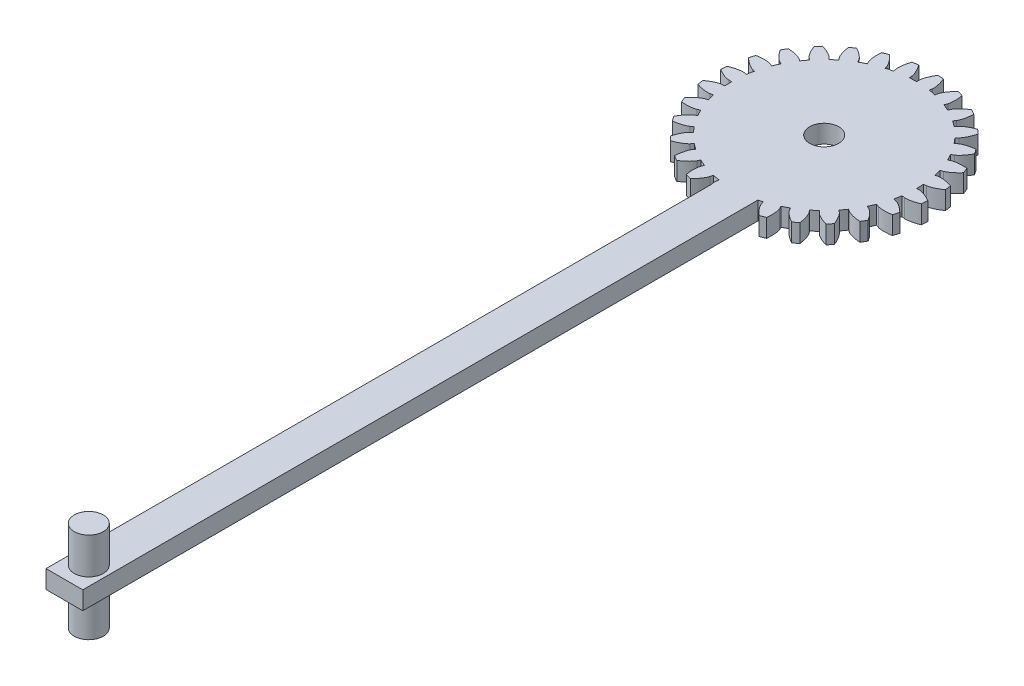
SolidWorks part; units mm, degrees
ref_plane "前视基准面" through (0, 0, 0) normal (0, 0, 1) x (1, 0, 0)
ref_plane "上视基准面" through (0, 0, 0) normal (0, 1, 0) x (1, 0, 0)
ref_plane "右视基准面" through (0, 0, 0) normal (1, 0, 0) x (0, 0, -1)
other "Configuration Table"
sketch "草图1" plane through (0, 0, 0) normal (0, 1, 0) x (1, 0, 0)
  line L0 (0, 0) -> (0.4992, 27.8082) construction
  line L1 (0, 0) -> (2.0715, 27.9233) construction
  line L2 (0, 0) -> (5.5923, 29.6778) construction
  circle A1 centre (0, 0) radius 30
  circle A2 centre (0, 0) radius 25.5
  circle A3 centre (0, 0) radius 28
  spline S0 degree 4 poles (0, 26.3114) (0.0005, 26.3327) (0.0033, 26.3925) (0.0143, 26.5052) (0.0405, 26.6883) (0.1066, 27.0262) (0.2428, 27.5315) (0.4372, 28.0765) (0.6818, 28.6409) (0.9223, 29.1277) (1.1281, 29.5103) (1.3926, 29.9661) (1.733, 30.5031) (2.1599, 31.113) (2.6837, 31.7862) (3.2497, 32.4456) (3.8445, 33.0787) (4.4662, 33.686) (5.1111, 34.2675) (5.6956, 34.7547) (6.2075, 35.1557) (6.6446, 35.4811) (6.994, 35.7325) (7.3574, 35.9834) (7.7076, 36.2182) (8.0916, 36.4641) (8.4279, 36.6743) (8.9316, 36.9744) (9.2362, 37.1482) (9.7285, 37.4218) (9.9511, 37.5362) (10.152, 37.643) (10.2116, 37.6724) (10.2551, 37.6949) (10.2786, 37.7071) knots 0 0 0 0 0 0.005377 0.015084 0.028532 0.04661 0.092111 0.146842 0.174209 0.201575 0.228941 0.256307 0.307035 0.361767 0.4165 0.471232 0.525964 0.580697 0.635429 0.690161 0.717528 0.744894 0.77226 0.799626 0.826992 0.854358 0.881725 0.909091 0.954545 0.977273 0.988636 0.994318 1 1 1 1 1 construction
  spline S1 degree 4 poles (0, 26.3114) (0.0005, 26.3327) (0.0033, 26.3925) (0.0143, 26.5052) (0.0405, 26.6883) (0.1066, 27.0262) (0.2428, 27.5315) (0.4372, 28.0765) (0.6818, 28.6409) (0.9571, 29.1981) (1.1516, 29.5526) (1.3012, 29.8077) (1.3986, 29.9674) knots 0 0 0 0 0 0.005377 0.015084 0.028532 0.04661 0.092111 0.146842 0.174209 0.201575 0.248726 0.248726 0.248726 0.248726 0.248726
  spline S2 degree 1 poles (0, 26.3114) (0, 25.5) knots 0 0 1 1
  spline S3 degree 1 poles (3.8825, 26.0234) (3.7628, 25.2209) knots 0 0 1 1
  spline S4 degree 4 poles (3.8825, 26.0234) (3.8852, 26.0445) (3.8912, 26.1041) (3.8969, 26.2172) (3.8981, 26.4022) (3.8826, 26.7461) (3.8224, 27.2659) (3.7106, 27.8337) (3.5519, 28.428) (3.3618, 29.0197) (3.2218, 29.3991) (3.1115, 29.6734) (3.0387, 29.8457) knots 0 0 0 0 0 0.005377 0.015084 0.028532 0.04661 0.092111 0.146842 0.174209 0.201575 0.248726 0.248726 0.248726 0.248726 0.248726
  spline S5 degree 1 poles (5.8548, 25.6517) (5.6743, 24.8607) knots 0 0 1 1
  spline S6 degree 4 poles (5.8548, 25.6517) (5.86, 25.6724) (5.8761, 25.7301) (5.9119, 25.8375) (5.9782, 26.0102) (6.1178, 26.3249) (6.363, 26.7872) (6.6738, 27.2753) (7.0379, 27.7711) (7.4303, 28.2531) (7.6988, 28.5554) (7.9014, 28.7708) (8.0319, 28.9048) knots 0 0 0 0 0 0.005377 0.015084 0.028532 0.04661 0.092111 0.146842 0.174209 0.201575 0.248726 0.248726 0.248726 0.248726 0.248726
  dimension "D1" = 56
  dimension "D2" = 60
  dimension "D3" = 51
  dimension "D4" = 3.214
  dimension "D5" = 9.643
sketch "草图2" plane through (0, 0, 0) normal (0, 1, 0) x (1, 0, 0)
  circle A0 centre (0, 0) radius 25.5 construction
  circle A1 centre (0, 0) radius 30 construction
  arc A2 (5.6743, 24.8607) -> (3.7628, 25.2209) centre (0, 0) ccw
  arc A3 (3.0387, 29.8457) -> (1.3986, 29.9674) centre (0, 0) ccw
  arc A4 (9.6038, 28.4212) -> (8.0319, 28.9048) centre (0, 0) ccw
  arc A5 (11.064, 22.9747) -> (9.2806, 23.7512) centre (0, 0) ccw
  arc A6 (15.6873, 25.5716) -> (14.2625, 26.3928) centre (0, 0) ccw
  arc A7 (15.899, 19.9367) -> (14.333, 21.0906) centre (0, 0) ccw
  arc A8 (20.9842, 21.4397) -> (19.7778, 22.5574) centre (0, 0) ccw
  arc A9 (19.9367, 15.899) -> (18.6668, 17.3724) centre (0, 0) ccw
  arc A10 (25.2289, 16.2328) -> (24.3015, 17.5909) centre (0, 0) ccw
  arc A11 (22.9747, 11.064) -> (22.0645, 12.7831) centre (0, 0) ccw
  arc A12 (28.2085, 10.2118) -> (27.6065, 11.7423) centre (0, 0) ccw
  arc A13 (24.8607, 5.6743) -> (24.3558, 7.5528) centre (0, 0) ccw
  arc A14 (29.7736, 3.6788) -> (29.5273, 5.3048) centre (0, 0) ccw
  arc A15 (25.5, 0) -> (25.4258, 1.9437) centre (0, 0) ccw
  arc A16 (29.8457, -3.0387) -> (29.9674, -1.3986) centre (0, 0) ccw
  arc A17 (24.8607, -5.6743) -> (25.2209, -3.7628) centre (0, 0) ccw
  arc A18 (28.4212, -9.6038) -> (28.9048, -8.0319) centre (0, 0) ccw
  arc A19 (22.9747, -11.064) -> (23.7512, -9.2806) centre (0, 0) ccw
  arc A20 (25.5716, -15.6873) -> (26.3928, -14.2625) centre (0, 0) ccw
  arc A21 (19.9367, -15.899) -> (21.0906, -14.333) centre (0, 0) ccw
  arc A22 (21.4397, -20.9842) -> (22.5574, -19.7778) centre (0, 0) ccw
  arc A23 (15.899, -19.9367) -> (17.3724, -18.6668) centre (0, 0) ccw
  arc A24 (16.2328, -25.2289) -> (17.5909, -24.3015) centre (0, 0) ccw
  arc A25 (11.064, -22.9747) -> (12.7831, -22.0645) centre (0, 0) ccw
  arc A26 (10.2118, -28.2085) -> (11.7423, -27.6065) centre (0, 0) ccw
  arc A27 (5.6743, -24.8607) -> (7.5528, -24.3558) centre (0, 0) ccw
  arc A28 (3.6788, -29.7736) -> (5.3048, -29.5273) centre (0, 0) ccw
  arc A29 (0, -25.5) -> (1.9437, -25.4258) centre (0, 0) ccw
  arc A30 (-3.0387, -29.8457) -> (-1.3986, -29.9674) centre (0, 0) ccw
  arc A31 (-5.6743, -24.8607) -> (-3.7628, -25.2209) centre (0, 0) ccw
  arc A32 (-9.6038, -28.4212) -> (-8.0319, -28.9048) centre (0, 0) ccw
  arc A33 (-11.064, -22.9747) -> (-9.2806, -23.7512) centre (0, 0) ccw
  arc A34 (-15.6873, -25.5716) -> (-14.2625, -26.3928) centre (0, 0) ccw
  arc A35 (-15.899, -19.9367) -> (-14.333, -21.0906) centre (0, 0) ccw
  arc A36 (-20.9842, -21.4397) -> (-19.7778, -22.5574) centre (0, 0) ccw
  arc A37 (-19.9367, -15.899) -> (-18.6668, -17.3724) centre (0, 0) ccw
  arc A38 (-25.2289, -16.2328) -> (-24.3015, -17.5909) centre (0, 0) ccw
  arc A39 (-22.9747, -11.064) -> (-22.0645, -12.7831) centre (0, 0) ccw
  arc A40 (-28.2085, -10.2118) -> (-27.6065, -11.7423) centre (0, 0) ccw
  arc A41 (-24.8607, -5.6743) -> (-24.3558, -7.5528) centre (0, 0) ccw
  arc A42 (-29.7736, -3.6788) -> (-29.5273, -5.3048) centre (0, 0) ccw
  arc A43 (-25.5, 0) -> (-25.4258, -1.9437) centre (0, 0) ccw
  arc A44 (-29.8457, 3.0387) -> (-29.9674, 1.3986) centre (0, 0) ccw
  arc A45 (-24.8607, 5.6743) -> (-25.2209, 3.7628) centre (0, 0) ccw
  arc A46 (-28.4212, 9.6038) -> (-28.9048, 8.0319) centre (0, 0) ccw
  arc A47 (-22.9747, 11.064) -> (-23.7512, 9.2806) centre (0, 0) ccw
  arc A48 (-25.5716, 15.6873) -> (-26.3928, 14.2625) centre (0, 0) ccw
  arc A49 (-19.9367, 15.899) -> (-21.0906, 14.333) centre (0, 0) ccw
  arc A50 (-21.4397, 20.9842) -> (-22.5574, 19.7778) centre (0, 0) ccw
  arc A51 (-15.899, 19.9367) -> (-17.3724, 18.6668) centre (0, 0) ccw
  arc A52 (-16.2328, 25.2289) -> (-17.5909, 24.3015) centre (0, 0) ccw
  arc A53 (-11.064, 22.9747) -> (-12.7831, 22.0645) centre (0, 0) ccw
  arc A54 (-10.2118, 28.2085) -> (-11.7423, 27.6065) centre (0, 0) ccw
  arc A55 (-5.6743, 24.8607) -> (-7.5528, 24.3558) centre (0, 0) ccw
  arc A56 (-3.6788, 29.7736) -> (-5.3048, 29.5273) centre (0, 0) ccw
  arc A57 (0, 25.5) -> (-1.9437, 25.4258) centre (0, 0) ccw
  spline S2 degree 1 poles (446.5585, 2993.172) (-438.9084, -2941.8952) knots -3697.329683 -3697.329683 3698.289139 3698.289139 only from (3.8825, 26.0234) to (3.7628, 25.2209) construction
  spline S3 degree 4 poles (-2963.5983, 460.6318) (-43.9294, 27.4595) (2.5359, 22.6625) (3.8865, 24.4837) (3.8981, 26.4022) (3.8826, 26.7461) (3.8224, 27.2659) (3.7106, 27.8337) (3.5519, 28.428) (-1.991, 45.6841) (-39.6557, 51.7161) (84.7425, 26.7975) (-2996.3003, -25.1272) knots -0.436845 -0.436845 -0.436845 -0.436845 -0.436845 0.005377 0.015084 0.028532 0.04661 0.092111 0.146842 0.174209 0.201575 4.659416 4.659416 4.659416 4.659416 4.659416 only from (3.8825, 26.0234) to (3.0387, 29.8457) construction
  spline S4 degree 1 poles (0, 3026.3002) (0, -2974.4559) knots -3697.329683 -3697.329683 3698.289139 3698.289139 only from (0, 26.3114) to (0, 25.5) construction
  spline S5 degree 4 poles (2999.1269, 18.2832) (47.5004, 20.6767) (0.8359, 22.7886) (-0.2312, 24.7892) (0.0405, 26.6883) (0.1066, 27.0262) (0.2428, 27.5315) (0.4372, 28.0765) (0.6818, 28.6409) (8.7103, 44.8902) (46.8528, 45.2984) (-79.8606, 39.0087) (2959.7927, -466.9838) knots -0.436845 -0.436845 -0.436845 -0.436845 -0.436845 0.005377 0.015084 0.028532 0.04661 0.092111 0.146842 0.174209 0.201575 4.659416 4.659416 4.659416 4.659416 4.659416 only from (0, 26.3114) to (1.3986, 29.9674) construction
  spline S6 degree 4 poles (5.8548, 25.6517) (5.86, 25.6724) (5.8761, 25.7301) (5.9119, 25.8375) (5.9782, 26.0102) (6.1178, 26.3249) (6.363, 26.7872) (6.6738, 27.2753) (7.0379, 27.7711) (7.4303, 28.2531) (7.6988, 28.5554) (7.9014, 28.7708) (8.0319, 28.9048) knots 0 0 0 0 0 0.005377 0.015084 0.028532 0.04661 0.092111 0.146842 0.174209 0.201575 0.248726 0.248726 0.248726 0.248726 0.248726
  spline S7 degree 1 poles (5.8548, 25.6517) (5.6743, 24.8607) knots 0 0 1 1
  spline S8 degree 1 poles (3.8825, 26.0234) (3.7628, 25.2209) knots 0 0 1 1
  spline S9 degree 4 poles (3.8825, 26.0234) (3.8852, 26.0445) (3.8912, 26.1041) (3.8969, 26.2172) (3.8981, 26.4022) (3.8826, 26.7461) (3.8224, 27.2659) (3.7106, 27.8337) (3.5519, 28.428) (3.3618, 29.0197) (3.2218, 29.3991) (3.1115, 29.6734) (3.0387, 29.8457) knots 0 0 0 0 0 0.005377 0.015084 0.028532 0.04661 0.092111 0.146842 0.174209 0.201575 0.248726 0.248726 0.248726 0.248726 0.248726
  spline S10 degree 1 poles (0, 26.3114) (0, 25.5) knots 0 0 1 1
  spline S11 degree 4 poles (0, 26.3114) (0.0005, 26.3327) (0.0033, 26.3925) (0.0143, 26.5052) (0.0405, 26.6883) (0.1066, 27.0262) (0.2428, 27.5315) (0.4372, 28.0765) (0.6818, 28.6409) (0.9571, 29.1981) (1.1516, 29.5526) (1.3012, 29.8077) (1.3986, 29.9674) knots 0 0 0 0 0 0.005377 0.015084 0.028532 0.04661 0.092111 0.146842 0.174209 0.201575 0.248726 0.248726 0.248726 0.248726 0.248726
  spline S12 degree 4 poles (9.5759, 24.507) (9.5832, 24.527) (9.6024, 24.5837) (9.6331, 24.6927) (9.6754, 24.8728) (9.7368, 25.2116) (9.7938, 25.7317) (9.8111, 26.3102) (9.7887, 26.9249) (9.7351, 27.5441) (9.6829, 27.945) (9.6364, 28.237) (9.6038, 28.4212) knots 0 0 0 0 0 0.005377 0.015084 0.028532 0.04661 0.092111 0.146842 0.174209 0.201575 0.248726 0.248726 0.248726 0.248726 0.248726
  spline S13 degree 1 poles (9.5759, 24.507) (9.2806, 23.7512) knots 0 0 1 1
  spline S14 degree 4 poles (11.4161, 23.7057) (11.4258, 23.7248) (11.4542, 23.7774) (11.5131, 23.8742) (11.6161, 24.0278) (11.8223, 24.3035) (12.1642, 24.6997) (12.5758, 25.1064) (13.0411, 25.5088) (13.5309, 25.8913) (13.8599, 26.1263) (14.1054, 26.2912) (14.2625, 26.3928) knots 0 0 0 0 0 0.005377 0.015084 0.028532 0.04661 0.092111 0.146842 0.174209 0.201575 0.248726 0.248726 0.248726 0.248726 0.248726
  spline S15 degree 1 poles (11.4161, 23.7057) (11.064, 22.9747) knots 0 0 1 1
  spline S16 degree 4 poles (14.7891, 21.7617) (14.8007, 21.7796) (14.832, 21.8306) (14.8862, 21.9301) (14.9675, 22.0962) (15.1028, 22.4128) (15.2741, 22.9072) (15.4197, 23.4673) (15.5346, 24.0716) (15.6201, 24.6872) (15.6585, 25.0898) (15.6781, 25.3848) (15.6873, 25.5716) knots 0 0 0 0 0 0.005377 0.015084 0.028532 0.04661 0.092111 0.146842 0.174209 0.201575 0.248726 0.248726 0.248726 0.248726 0.248726
  spline S17 degree 1 poles (14.7891, 21.7617) (14.333, 21.0906) knots 0 0 1 1
  spline S18 degree 4 poles (16.4049, 20.5711) (16.4186, 20.5875) (16.458, 20.6325) (16.5369, 20.7137) (16.6716, 20.8405) (16.9339, 21.0635) (17.3554, 21.3736) (17.8472, 21.6785) (18.3904, 21.9673) (18.953, 22.2313) (19.3261, 22.3872) (19.6021, 22.4933) (19.7778, 22.5574) knots 0 0 0 0 0 0.005377 0.015084 0.028532 0.04661 0.092111 0.146842 0.174209 0.201575 0.248726 0.248726 0.248726 0.248726 0.248726
  spline S19 degree 1 poles (16.4049, 20.5711) (15.899, 19.9367) knots 0 0 1 1
  spline S20 degree 4 poles (19.2608, 17.9252) (19.2761, 17.9401) (19.3179, 17.9828) (19.3929, 18.0677) (19.5091, 18.2116) (19.7114, 18.4902) (19.9885, 18.9341) (20.2551, 19.4478) (20.5016, 20.0113) (20.7219, 20.5925) (20.8489, 20.9764) (20.9337, 21.2596) (20.9842, 21.4397) knots 0 0 0 0 0 0.005377 0.015084 0.028532 0.04661 0.092111 0.146842 0.174209 0.201575 0.248726 0.248726 0.248726 0.248726 0.248726
  spline S21 degree 1 poles (19.2608, 17.9252) (18.6668, 17.3724) knots 0 0 1 1
  spline S22 degree 4 poles (20.5711, 16.4049) (20.588, 16.4178) (20.6365, 16.4529) (20.7315, 16.5146) (20.891, 16.6082) (21.1964, 16.7672) (21.6763, 16.9758) (22.2237, 17.1636) (22.8175, 17.3243) (23.4248, 17.4565) (23.8232, 17.5254) (24.1159, 17.5675) (24.3015, 17.5909) knots 0 0 0 0 0 0.005377 0.015084 0.028532 0.04661 0.092111 0.146842 0.174209 0.201575 0.248726 0.248726 0.248726 0.248726 0.248726
  spline S23 degree 1 poles (20.5711, 16.4049) (19.9367, 15.899) knots 0 0 1 1
  spline S24 degree 4 poles (22.7666, 13.1899) (22.7848, 13.201) (22.8351, 13.2333) (22.9271, 13.2994) (23.0724, 13.4139) (23.3317, 13.6404) (23.7006, 14.0115) (24.0748, 14.453) (24.4405, 14.9476) (24.7846, 15.4651) (24.9939, 15.8111) (25.1396, 16.0684) (25.2289, 16.2328) knots 0 0 0 0 0 0.005377 0.015084 0.028532 0.04661 0.092111 0.146842 0.174209 0.201575 0.248726 0.248726 0.248726 0.248726 0.248726
  spline S25 degree 1 poles (22.7666, 13.1899) (22.0645, 12.7831) knots 0 0 1 1
  spline S26 degree 4 poles (23.7057, 11.4161) (23.7252, 11.4249) (23.7802, 11.4483) (23.8866, 11.4873) (24.0629, 11.5431) (24.396, 11.6302) (24.9103, 11.7267) (25.4858, 11.7881) (26.1004, 11.8126) (26.7219, 11.8063) (27.1257, 11.7849) (27.4204, 11.7607) (27.6065, 11.7423) knots 0 0 0 0 0 0.005377 0.015084 0.028532 0.04661 0.092111 0.146842 0.174209 0.201575 0.248726 0.248726 0.248726 0.248726 0.248726
  spline S27 degree 1 poles (23.7057, 11.4161) (22.9747, 11.064) knots 0 0 1 1
  spline S28 degree 4 poles (25.1308, 7.7931) (25.151, 7.7999) (25.2073, 7.8203) (25.3117, 7.8642) (25.4788, 7.9434) (25.782, 8.1066) (26.2242, 8.3863) (26.6872, 8.7335) (27.1539, 9.1343) (27.6045, 9.5623) (27.8855, 9.853) (28.0848, 10.0715) (28.2085, 10.2118) knots 0 0 0 0 0 0.005377 0.015084 0.028532 0.04661 0.092111 0.146842 0.174209 0.201575 0.248726 0.248726 0.248726 0.248726 0.248726
  spline S29 degree 1 poles (25.1308, 7.7931) (24.3558, 7.5528) knots 0 0 1 1
  spline S30 degree 4 poles (25.6517, 5.8548) (25.6726, 5.8591) (25.7315, 5.8697) (25.8439, 5.884) (26.0282, 5.8992) (26.3723, 5.91) (26.8952, 5.8897) (27.4699, 5.8214) (28.0746, 5.7085) (28.6791, 5.5641) (29.0679, 5.4534) (29.3499, 5.3643) (29.5273, 5.3048) knots 0 0 0 0 0 0.005377 0.015084 0.028532 0.04661 0.092111 0.146842 0.174209 0.201575 0.248726 0.248726 0.248726 0.248726 0.248726
  spline S31 degree 1 poles (25.6517, 5.8548) (24.8607, 5.6743) knots 0 0 1 1
  spline S32 degree 4 poles (26.2348, 2.0056) (26.2561, 2.0077) (26.3155, 2.015) (26.427, 2.0346) (26.6076, 2.0747) (26.9395, 2.1663) (27.4329, 2.3406) (27.9615, 2.576) (28.5056, 2.863) (29.0402, 3.1799) (29.3789, 3.4009) (29.6218, 3.5695) (29.7736, 3.6788) knots 0 0 0 0 0 0.005377 0.015084 0.028532 0.04661 0.092111 0.146842 0.174209 0.201575 0.248726 0.248726 0.248726 0.248726 0.248726
  spline S33 degree 1 poles (26.2348, 2.0056) (25.4258, 1.9437) knots 0 0 1 1
  spline S34 degree 4 poles (26.3114, 0) (26.3327, -0.0005) (26.3925, -0.0033) (26.5052, -0.0143) (26.6883, -0.0405) (27.0262, -0.1066) (27.5315, -0.2428) (28.0765, -0.4372) (28.6409, -0.6818) (29.1981, -0.9571) (29.5526, -1.1516) (29.8077, -1.3012) (29.9674, -1.3986) knots 0 0 0 0 0 0.005377 0.015084 0.028532 0.04661 0.092111 0.146842 0.174209 0.201575 0.248726 0.248726 0.248726 0.248726 0.248726
  spline S35 degree 1 poles (26.3114, 0) (25.5, 0) knots 0 0 1 1
  spline S36 degree 4 poles (26.0234, -3.8825) (26.0445, -3.8852) (26.1041, -3.8912) (26.2172, -3.8969) (26.4022, -3.8981) (26.7461, -3.8826) (27.2659, -3.8224) (27.8337, -3.7106) (28.428, -3.5519) (29.0197, -3.3618) (29.3991, -3.2218) (29.6734, -3.1115) (29.8457, -3.0387) knots 0 0 0 0 0 0.005377 0.015084 0.028532 0.04661 0.092111 0.146842 0.174209 0.201575 0.248726 0.248726 0.248726 0.248726 0.248726
  spline S37 degree 1 poles (26.0234, -3.8825) (25.2209, -3.7628) knots 0 0 1 1
  spline S38 degree 4 poles (25.6517, -5.8548) (25.6724, -5.86) (25.7301, -5.8761) (25.8375, -5.9119) (26.0102, -5.9782) (26.3249, -6.1178) (26.7872, -6.363) (27.2753, -6.6738) (27.7711, -7.0379) (28.2531, -7.4303) (28.5554, -7.6988) (28.7708, -7.9014) (28.9048, -8.0319) knots 0 0 0 0 0 0.005377 0.015084 0.028532 0.04661 0.092111 0.146842 0.174209 0.201575 0.248726 0.248726 0.248726 0.248726 0.248726
  spline S39 degree 1 poles (25.6517, -5.8548) (24.8607, -5.6743) knots 0 0 1 1
  spline S40 degree 4 poles (24.507, -9.5759) (24.527, -9.5832) (24.5837, -9.6024) (24.6927, -9.6331) (24.8728, -9.6754) (25.2116, -9.7368) (25.7317, -9.7938) (26.3102, -9.8111) (26.9249, -9.7887) (27.5441, -9.7351) (27.945, -9.6829) (28.237, -9.6364) (28.4212, -9.6038) knots 0 0 0 0 0 0.005377 0.015084 0.028532 0.04661 0.092111 0.146842 0.174209 0.201575 0.248726 0.248726 0.248726 0.248726 0.248726
  spline S41 degree 1 poles (24.507, -9.5759) (23.7512, -9.2806) knots 0 0 1 1
  spline S42 degree 4 poles (23.7057, -11.4161) (23.7248, -11.4258) (23.7774, -11.4542) (23.8742, -11.5131) (24.0278, -11.6161) (24.3035, -11.8223) (24.6997, -12.1642) (25.1064, -12.5758) (25.5088, -13.0411) (25.8913, -13.5309) (26.1263, -13.8599) (26.2912, -14.1054) (26.3928, -14.2625) knots 0 0 0 0 0 0.005377 0.015084 0.028532 0.04661 0.092111 0.146842 0.174209 0.201575 0.248726 0.248726 0.248726 0.248726 0.248726
  spline S43 degree 1 poles (23.7057, -11.4161) (22.9747, -11.064) knots 0 0 1 1
  spline S44 degree 4 poles (21.7617, -14.7891) (21.7796, -14.8007) (21.8306, -14.832) (21.9301, -14.8862) (22.0962, -14.9675) (22.4128, -15.1028) (22.9072, -15.2741) (23.4673, -15.4197) (24.0716, -15.5346) (24.6872, -15.6201) (25.0898, -15.6585) (25.3848, -15.6781) (25.5716, -15.6873) knots 0 0 0 0 0 0.005377 0.015084 0.028532 0.04661 0.092111 0.146842 0.174209 0.201575 0.248726 0.248726 0.248726 0.248726 0.248726
  spline S45 degree 1 poles (21.7617, -14.7891) (21.0906, -14.333) knots 0 0 1 1
  spline S46 degree 4 poles (20.5711, -16.4049) (20.5875, -16.4186) (20.6325, -16.458) (20.7137, -16.5369) (20.8405, -16.6716) (21.0635, -16.9339) (21.3736, -17.3554) (21.6785, -17.8472) (21.9673, -18.3904) (22.2313, -18.953) (22.3872, -19.3261) (22.4933, -19.6021) (22.5574, -19.7778) knots 0 0 0 0 0 0.005377 0.015084 0.028532 0.04661 0.092111 0.146842 0.174209 0.201575 0.248726 0.248726 0.248726 0.248726 0.248726
  spline S47 degree 1 poles (20.5711, -16.4049) (19.9367, -15.899) knots 0 0 1 1
  spline S48 degree 4 poles (17.9252, -19.2608) (17.9401, -19.2761) (17.9828, -19.3179) (18.0677, -19.3929) (18.2116, -19.5091) (18.4902, -19.7114) (18.9341, -19.9885) (19.4478, -20.2551) (20.0113, -20.5016) (20.5925, -20.7219) (20.9764, -20.8489) (21.2596, -20.9337) (21.4397, -20.9842) knots 0 0 0 0 0 0.005377 0.015084 0.028532 0.04661 0.092111 0.146842 0.174209 0.201575 0.248726 0.248726 0.248726 0.248726 0.248726
  spline S49 degree 1 poles (17.9252, -19.2608) (17.3724, -18.6668) knots 0 0 1 1
  spline S50 degree 4 poles (16.4049, -20.5711) (16.4178, -20.588) (16.4529, -20.6365) (16.5146, -20.7315) (16.6082, -20.891) (16.7672, -21.1964) (16.9758, -21.6763) (17.1636, -22.2237) (17.3243, -22.8175) (17.4565, -23.4248) (17.5254, -23.8232) (17.5675, -24.1159) (17.5909, -24.3015) knots 0 0 0 0 0 0.005377 0.015084 0.028532 0.04661 0.092111 0.146842 0.174209 0.201575 0.248726 0.248726 0.248726 0.248726 0.248726
  spline S51 degree 1 poles (16.4049, -20.5711) (15.899, -19.9367) knots 0 0 1 1
  spline S52 degree 4 poles (13.1899, -22.7666) (13.201, -22.7848) (13.2333, -22.8351) (13.2994, -22.9271) (13.4139, -23.0724) (13.6404, -23.3317) (14.0115, -23.7006) (14.453, -24.0748) (14.9476, -24.4405) (15.4651, -24.7846) (15.8111, -24.9939) (16.0684, -25.1396) (16.2328, -25.2289) knots 0 0 0 0 0 0.005377 0.015084 0.028532 0.04661 0.092111 0.146842 0.174209 0.201575 0.248726 0.248726 0.248726 0.248726 0.248726
  spline S53 degree 1 poles (13.1899, -22.7666) (12.7831, -22.0645) knots 0 0 1 1
  spline S54 degree 4 poles (11.4161, -23.7057) (11.4249, -23.7252) (11.4483, -23.7802) (11.4873, -23.8866) (11.5431, -24.0629) (11.6302, -24.396) (11.7267, -24.9103) (11.7881, -25.4858) (11.8126, -26.1004) (11.8063, -26.7219) (11.7849, -27.1257) (11.7607, -27.4204) (11.7423, -27.6065) knots 0 0 0 0 0 0.005377 0.015084 0.028532 0.04661 0.092111 0.146842 0.174209 0.201575 0.248726 0.248726 0.248726 0.248726 0.248726
  spline S55 degree 1 poles (11.4161, -23.7057) (11.064, -22.9747) knots 0 0 1 1
  spline S56 degree 4 poles (7.7931, -25.1308) (7.7999, -25.151) (7.8203, -25.2073) (7.8642, -25.3117) (7.9434, -25.4788) (8.1066, -25.782) (8.3863, -26.2242) (8.7335, -26.6872) (9.1343, -27.1539) (9.5623, -27.6045) (9.853, -27.8855) (10.0715, -28.0848) (10.2118, -28.2085) knots 0 0 0 0 0 0.005377 0.015084 0.028532 0.04661 0.092111 0.146842 0.174209 0.201575 0.248726 0.248726 0.248726 0.248726 0.248726
  spline S57 degree 1 poles (7.7931, -25.1308) (7.5528, -24.3558) knots 0 0 1 1
  spline S58 degree 4 poles (5.8548, -25.6517) (5.8591, -25.6726) (5.8697, -25.7315) (5.884, -25.8439) (5.8992, -26.0282) (5.91, -26.3723) (5.8897, -26.8952) (5.8214, -27.4699) (5.7085, -28.0746) (5.5641, -28.6791) (5.4534, -29.0679) (5.3643, -29.3499) (5.3048, -29.5273) knots 0 0 0 0 0 0.005377 0.015084 0.028532 0.04661 0.092111 0.146842 0.174209 0.201575 0.248726 0.248726 0.248726 0.248726 0.248726
  spline S59 degree 1 poles (5.8548, -25.6517) (5.6743, -24.8607) knots 0 0 1 1
  spline S60 degree 4 poles (2.0056, -26.2348) (2.0077, -26.2561) (2.015, -26.3155) (2.0346, -26.427) (2.0747, -26.6076) (2.1663, -26.9395) (2.3406, -27.4329) (2.576, -27.9615) (2.863, -28.5056) (3.1799, -29.0402) (3.4009, -29.3789) (3.5695, -29.6218) (3.6788, -29.7736) knots 0 0 0 0 0 0.005377 0.015084 0.028532 0.04661 0.092111 0.146842 0.174209 0.201575 0.248726 0.248726 0.248726 0.248726 0.248726
  spline S61 degree 1 poles (2.0056, -26.2348) (1.9437, -25.4258) knots 0 0 1 1
  spline S62 degree 4 poles (0, -26.3114) (-0.0005, -26.3327) (-0.0033, -26.3925) (-0.0143, -26.5052) (-0.0405, -26.6883) (-0.1066, -27.0262) (-0.2428, -27.5315) (-0.4372, -28.0765) (-0.6818, -28.6409) (-0.9571, -29.1981) (-1.1516, -29.5526) (-1.3012, -29.8077) (-1.3986, -29.9674) knots 0 0 0 0 0 0.005377 0.015084 0.028532 0.04661 0.092111 0.146842 0.174209 0.201575 0.248726 0.248726 0.248726 0.248726 0.248726
  spline S63 degree 1 poles (0, -26.3114) (0, -25.5) knots 0 0 1 1
  spline S64 degree 4 poles (-3.8825, -26.0234) (-3.8852, -26.0445) (-3.8912, -26.1041) (-3.8969, -26.2172) (-3.8981, -26.4022) (-3.8826, -26.7461) (-3.8224, -27.2659) (-3.7106, -27.8337) (-3.5519, -28.428) (-3.3618, -29.0197) (-3.2218, -29.3991) (-3.1115, -29.6734) (-3.0387, -29.8457) knots 0 0 0 0 0 0.005377 0.015084 0.028532 0.04661 0.092111 0.146842 0.174209 0.201575 0.248726 0.248726 0.248726 0.248726 0.248726
  spline S65 degree 1 poles (-3.8825, -26.0234) (-3.7628, -25.2209) knots 0 0 1 1
  spline S66 degree 4 poles (-5.8548, -25.6517) (-5.86, -25.6724) (-5.8761, -25.7301) (-5.9119, -25.8375) (-5.9782, -26.0102) (-6.1178, -26.3249) (-6.363, -26.7872) (-6.6738, -27.2753) (-7.0379, -27.7711) (-7.4303, -28.2531) (-7.6988, -28.5554) (-7.9014, -28.7708) (-8.0319, -28.9048) knots 0 0 0 0 0 0.005377 0.015084 0.028532 0.04661 0.092111 0.146842 0.174209 0.201575 0.248726 0.248726 0.248726 0.248726 0.248726
  spline S67 degree 1 poles (-5.8548, -25.6517) (-5.6743, -24.8607) knots 0 0 1 1
  spline S68 degree 4 poles (-9.5759, -24.507) (-9.5832, -24.527) (-9.6024, -24.5837) (-9.6331, -24.6927) (-9.6754, -24.8728) (-9.7368, -25.2116) (-9.7938, -25.7317) (-9.8111, -26.3102) (-9.7887, -26.9249) (-9.7351, -27.5441) (-9.6829, -27.945) (-9.6364, -28.237) (-9.6038, -28.4212) knots 0 0 0 0 0 0.005377 0.015084 0.028532 0.04661 0.092111 0.146842 0.174209 0.201575 0.248726 0.248726 0.248726 0.248726 0.248726
  spline S69 degree 1 poles (-9.5759, -24.507) (-9.2806, -23.7512) knots 0 0 1 1
  spline S70 degree 4 poles (-11.4161, -23.7057) (-11.4258, -23.7248) (-11.4542, -23.7774) (-11.5131, -23.8742) (-11.6161, -24.0278) (-11.8223, -24.3035) (-12.1642, -24.6997) (-12.5758, -25.1064) (-13.0411, -25.5088) (-13.5309, -25.8913) (-13.8599, -26.1263) (-14.1054, -26.2912) (-14.2625, -26.3928) knots 0 0 0 0 0 0.005377 0.015084 0.028532 0.04661 0.092111 0.146842 0.174209 0.201575 0.248726 0.248726 0.248726 0.248726 0.248726
  spline S71 degree 1 poles (-11.4161, -23.7057) (-11.064, -22.9747) knots 0 0 1 1
  spline S72 degree 4 poles (-14.7891, -21.7617) (-14.8007, -21.7796) (-14.832, -21.8306) (-14.8862, -21.9301) (-14.9675, -22.0962) (-15.1028, -22.4128) (-15.2741, -22.9072) (-15.4197, -23.4673) (-15.5346, -24.0716) (-15.6201, -24.6872) (-15.6585, -25.0898) (-15.6781, -25.3848) (-15.6873, -25.5716) knots 0 0 0 0 0 0.005377 0.015084 0.028532 0.04661 0.092111 0.146842 0.174209 0.201575 0.248726 0.248726 0.248726 0.248726 0.248726
  spline S73 degree 1 poles (-14.7891, -21.7617) (-14.333, -21.0906) knots 0 0 1 1
  spline S74 degree 4 poles (-16.4049, -20.5711) (-16.4186, -20.5875) (-16.458, -20.6325) (-16.5369, -20.7137) (-16.6716, -20.8405) (-16.9339, -21.0635) (-17.3554, -21.3736) (-17.8472, -21.6785) (-18.3904, -21.9673) (-18.953, -22.2313) (-19.3261, -22.3872) (-19.6021, -22.4933) (-19.7778, -22.5574) knots 0 0 0 0 0 0.005377 0.015084 0.028532 0.04661 0.092111 0.146842 0.174209 0.201575 0.248726 0.248726 0.248726 0.248726 0.248726
  spline S75 degree 1 poles (-16.4049, -20.5711) (-15.899, -19.9367) knots 0 0 1 1
  spline S76 degree 4 poles (-19.2608, -17.9252) (-19.2761, -17.9401) (-19.3179, -17.9828) (-19.3929, -18.0677) (-19.5091, -18.2116) (-19.7114, -18.4902) (-19.9885, -18.9341) (-20.2551, -19.4478) (-20.5016, -20.0113) (-20.7219, -20.5925) (-20.8489, -20.9764) (-20.9337, -21.2596) (-20.9842, -21.4397) knots 0 0 0 0 0 0.005377 0.015084 0.028532 0.04661 0.092111 0.146842 0.174209 0.201575 0.248726 0.248726 0.248726 0.248726 0.248726
  spline S77 degree 1 poles (-19.2608, -17.9252) (-18.6668, -17.3724) knots 0 0 1 1
  spline S78 degree 4 poles (-20.5711, -16.4049) (-20.588, -16.4178) (-20.6365, -16.4529) (-20.7315, -16.5146) (-20.891, -16.6082) (-21.1964, -16.7672) (-21.6763, -16.9758) (-22.2237, -17.1636) (-22.8175, -17.3243) (-23.4248, -17.4565) (-23.8232, -17.5254) (-24.1159, -17.5675) (-24.3015, -17.5909) knots 0 0 0 0 0 0.005377 0.015084 0.028532 0.04661 0.092111 0.146842 0.174209 0.201575 0.248726 0.248726 0.248726 0.248726 0.248726
  spline S79 degree 1 poles (-20.5711, -16.4049) (-19.9367, -15.899) knots 0 0 1 1
  spline S80 degree 4 poles (-22.7666, -13.1899) (-22.7848, -13.201) (-22.8351, -13.2333) (-22.9271, -13.2994) (-23.0724, -13.4139) (-23.3317, -13.6404) (-23.7006, -14.0115) (-24.0748, -14.453) (-24.4405, -14.9476) (-24.7846, -15.4651) (-24.9939, -15.8111) (-25.1396, -16.0684) (-25.2289, -16.2328) knots 0 0 0 0 0 0.005377 0.015084 0.028532 0.04661 0.092111 0.146842 0.174209 0.201575 0.248726 0.248726 0.248726 0.248726 0.248726
  spline S81 degree 1 poles (-22.7666, -13.1899) (-22.0645, -12.7831) knots 0 0 1 1
  spline S82 degree 4 poles (-23.7057, -11.4161) (-23.7252, -11.4249) (-23.7802, -11.4483) (-23.8866, -11.4873) (-24.0629, -11.5431) (-24.396, -11.6302) (-24.9103, -11.7267) (-25.4858, -11.7881) (-26.1004, -11.8126) (-26.7219, -11.8063) (-27.1257, -11.7849) (-27.4204, -11.7607) (-27.6065, -11.7423) knots 0 0 0 0 0 0.005377 0.015084 0.028532 0.04661 0.092111 0.146842 0.174209 0.201575 0.248726 0.248726 0.248726 0.248726 0.248726
  spline S83 degree 1 poles (-23.7057, -11.4161) (-22.9747, -11.064) knots 0 0 1 1
  spline S84 degree 4 poles (-25.1308, -7.7931) (-25.151, -7.7999) (-25.2073, -7.8203) (-25.3117, -7.8642) (-25.4788, -7.9434) (-25.782, -8.1066) (-26.2242, -8.3863) (-26.6872, -8.7335) (-27.1539, -9.1343) (-27.6045, -9.5623) (-27.8855, -9.853) (-28.0848, -10.0715) (-28.2085, -10.2118) knots 0 0 0 0 0 0.005377 0.015084 0.028532 0.04661 0.092111 0.146842 0.174209 0.201575 0.248726 0.248726 0.248726 0.248726 0.248726
  spline S85 degree 1 poles (-25.1308, -7.7931) (-24.3558, -7.5528) knots 0 0 1 1
  spline S86 degree 4 poles (-25.6517, -5.8548) (-25.6726, -5.8591) (-25.7315, -5.8697) (-25.8439, -5.884) (-26.0282, -5.8992) (-26.3723, -5.91) (-26.8952, -5.8897) (-27.4699, -5.8214) (-28.0746, -5.7085) (-28.6791, -5.5641) (-29.0679, -5.4534) (-29.3499, -5.3643) (-29.5273, -5.3048) knots 0 0 0 0 0 0.005377 0.015084 0.028532 0.04661 0.092111 0.146842 0.174209 0.201575 0.248726 0.248726 0.248726 0.248726 0.248726
  spline S87 degree 1 poles (-25.6517, -5.8548) (-24.8607, -5.6743) knots 0 0 1 1
  spline S88 degree 4 poles (-26.2348, -2.0056) (-26.2561, -2.0077) (-26.3155, -2.015) (-26.427, -2.0346) (-26.6076, -2.0747) (-26.9395, -2.1663) (-27.4329, -2.3406) (-27.9615, -2.576) (-28.5056, -2.863) (-29.0402, -3.1799) (-29.3789, -3.4009) (-29.6218, -3.5695) (-29.7736, -3.6788) knots 0 0 0 0 0 0.005377 0.015084 0.028532 0.04661 0.092111 0.146842 0.174209 0.201575 0.248726 0.248726 0.248726 0.248726 0.248726
  spline S89 degree 1 poles (-26.2348, -2.0056) (-25.4258, -1.9437) knots 0 0 1 1
  spline S90 degree 4 poles (-26.3114, 0) (-26.3327, 0.0005) (-26.3925, 0.0033) (-26.5052, 0.0143) (-26.6883, 0.0405) (-27.0262, 0.1066) (-27.5315, 0.2428) (-28.0765, 0.4372) (-28.6409, 0.6818) (-29.1981, 0.9571) (-29.5526, 1.1516) (-29.8077, 1.3012) (-29.9674, 1.3986) knots 0 0 0 0 0 0.005377 0.015084 0.028532 0.04661 0.092111 0.146842 0.174209 0.201575 0.248726 0.248726 0.248726 0.248726 0.248726
  spline S91 degree 1 poles (-26.3114, 0) (-25.5, 0) knots 0 0 1 1
  spline S92 degree 4 poles (-26.0234, 3.8825) (-26.0445, 3.8852) (-26.1041, 3.8912) (-26.2172, 3.8969) (-26.4022, 3.8981) (-26.7461, 3.8826) (-27.2659, 3.8224) (-27.8337, 3.7106) (-28.428, 3.5519) (-29.0197, 3.3618) (-29.3991, 3.2218) (-29.6734, 3.1115) (-29.8457, 3.0387) knots 0 0 0 0 0 0.005377 0.015084 0.028532 0.04661 0.092111 0.146842 0.174209 0.201575 0.248726 0.248726 0.248726 0.248726 0.248726
  spline S93 degree 1 poles (-26.0234, 3.8825) (-25.2209, 3.7628) knots 0 0 1 1
  spline S94 degree 4 poles (-25.6517, 5.8548) (-25.6724, 5.86) (-25.7301, 5.8761) (-25.8375, 5.9119) (-26.0102, 5.9782) (-26.3249, 6.1178) (-26.7872, 6.363) (-27.2753, 6.6738) (-27.7711, 7.0379) (-28.2531, 7.4303) (-28.5554, 7.6988) (-28.7708, 7.9014) (-28.9048, 8.0319) knots 0 0 0 0 0 0.005377 0.015084 0.028532 0.04661 0.092111 0.146842 0.174209 0.201575 0.248726 0.248726 0.248726 0.248726 0.248726
  spline S95 degree 1 poles (-25.6517, 5.8548) (-24.8607, 5.6743) knots 0 0 1 1
  spline S96 degree 4 poles (-24.507, 9.5759) (-24.527, 9.5832) (-24.5837, 9.6024) (-24.6927, 9.6331) (-24.8728, 9.6754) (-25.2116, 9.7368) (-25.7317, 9.7938) (-26.3102, 9.8111) (-26.9249, 9.7887) (-27.5441, 9.7351) (-27.945, 9.6829) (-28.237, 9.6364) (-28.4212, 9.6038) knots 0 0 0 0 0 0.005377 0.015084 0.028532 0.04661 0.092111 0.146842 0.174209 0.201575 0.248726 0.248726 0.248726 0.248726 0.248726
  spline S97 degree 1 poles (-24.507, 9.5759) (-23.7512, 9.2806) knots 0 0 1 1
  spline S98 degree 4 poles (-23.7057, 11.4161) (-23.7248, 11.4258) (-23.7774, 11.4542) (-23.8742, 11.5131) (-24.0278, 11.6161) (-24.3035, 11.8223) (-24.6997, 12.1642) (-25.1064, 12.5758) (-25.5088, 13.0411) (-25.8913, 13.5309) (-26.1263, 13.8599) (-26.2912, 14.1054) (-26.3928, 14.2625) knots 0 0 0 0 0 0.005377 0.015084 0.028532 0.04661 0.092111 0.146842 0.174209 0.201575 0.248726 0.248726 0.248726 0.248726 0.248726
  spline S99 degree 1 poles (-23.7057, 11.4161) (-22.9747, 11.064) knots 0 0 1 1
  spline S100 degree 4 poles (-21.7617, 14.7891) (-21.7796, 14.8007) (-21.8306, 14.832) (-21.9301, 14.8862) (-22.0962, 14.9675) (-22.4128, 15.1028) (-22.9072, 15.2741) (-23.4673, 15.4197) (-24.0716, 15.5346) (-24.6872, 15.6201) (-25.0898, 15.6585) (-25.3848, 15.6781) (-25.5716, 15.6873) knots 0 0 0 0 0 0.005377 0.015084 0.028532 0.04661 0.092111 0.146842 0.174209 0.201575 0.248726 0.248726 0.248726 0.248726 0.248726
  spline S101 degree 1 poles (-21.7617, 14.7891) (-21.0906, 14.333) knots 0 0 1 1
  spline S102 degree 4 poles (-20.5711, 16.4049) (-20.5875, 16.4186) (-20.6325, 16.458) (-20.7137, 16.5369) (-20.8405, 16.6716) (-21.0635, 16.9339) (-21.3736, 17.3554) (-21.6785, 17.8472) (-21.9673, 18.3904) (-22.2313, 18.953) (-22.3872, 19.3261) (-22.4933, 19.6021) (-22.5574, 19.7778) knots 0 0 0 0 0 0.005377 0.015084 0.028532 0.04661 0.092111 0.146842 0.174209 0.201575 0.248726 0.248726 0.248726 0.248726 0.248726
  spline S103 degree 1 poles (-20.5711, 16.4049) (-19.9367, 15.899) knots 0 0 1 1
  spline S104 degree 4 poles (-17.9252, 19.2608) (-17.9401, 19.2761) (-17.9828, 19.3179) (-18.0677, 19.3929) (-18.2116, 19.5091) (-18.4902, 19.7114) (-18.9341, 19.9885) (-19.4478, 20.2551) (-20.0113, 20.5016) (-20.5925, 20.7219) (-20.9764, 20.8489) (-21.2596, 20.9337) (-21.4397, 20.9842) knots 0 0 0 0 0 0.005377 0.015084 0.028532 0.04661 0.092111 0.146842 0.174209 0.201575 0.248726 0.248726 0.248726 0.248726 0.248726
  spline S105 degree 1 poles (-17.9252, 19.2608) (-17.3724, 18.6668) knots 0 0 1 1
  spline S106 degree 4 poles (-16.4049, 20.5711) (-16.4178, 20.588) (-16.4529, 20.6365) (-16.5146, 20.7315) (-16.6082, 20.891) (-16.7672, 21.1964) (-16.9758, 21.6763) (-17.1636, 22.2237) (-17.3243, 22.8175) (-17.4565, 23.4248) (-17.5254, 23.8232) (-17.5675, 24.1159) (-17.5909, 24.3015) knots 0 0 0 0 0 0.005377 0.015084 0.028532 0.04661 0.092111 0.146842 0.174209 0.201575 0.248726 0.248726 0.248726 0.248726 0.248726
  spline S107 degree 1 poles (-16.4049, 20.5711) (-15.899, 19.9367) knots 0 0 1 1
  spline S108 degree 4 poles (-13.1899, 22.7666) (-13.201, 22.7848) (-13.2333, 22.8351) (-13.2994, 22.9271) (-13.4139, 23.0724) (-13.6404, 23.3317) (-14.0115, 23.7006) (-14.453, 24.0748) (-14.9476, 24.4405) (-15.4651, 24.7846) (-15.8111, 24.9939) (-16.0684, 25.1396) (-16.2328, 25.2289) knots 0 0 0 0 0 0.005377 0.015084 0.028532 0.04661 0.092111 0.146842 0.174209 0.201575 0.248726 0.248726 0.248726 0.248726 0.248726
  spline S109 degree 1 poles (-13.1899, 22.7666) (-12.7831, 22.0645) knots 0 0 1 1
  spline S110 degree 4 poles (-11.4161, 23.7057) (-11.4249, 23.7252) (-11.4483, 23.7802) (-11.4873, 23.8866) (-11.5431, 24.0629) (-11.6302, 24.396) (-11.7267, 24.9103) (-11.7881, 25.4858) (-11.8126, 26.1004) (-11.8063, 26.7219) (-11.7849, 27.1257) (-11.7607, 27.4204) (-11.7423, 27.6065) knots 0 0 0 0 0 0.005377 0.015084 0.028532 0.04661 0.092111 0.146842 0.174209 0.201575 0.248726 0.248726 0.248726 0.248726 0.248726
  spline S111 degree 1 poles (-11.4161, 23.7057) (-11.064, 22.9747) knots 0 0 1 1
  spline S112 degree 4 poles (-7.7931, 25.1308) (-7.7999, 25.151) (-7.8203, 25.2073) (-7.8642, 25.3117) (-7.9434, 25.4788) (-8.1066, 25.782) (-8.3863, 26.2242) (-8.7335, 26.6872) (-9.1343, 27.1539) (-9.5623, 27.6045) (-9.853, 27.8855) (-10.0715, 28.0848) (-10.2118, 28.2085) knots 0 0 0 0 0 0.005377 0.015084 0.028532 0.04661 0.092111 0.146842 0.174209 0.201575 0.248726 0.248726 0.248726 0.248726 0.248726
  spline S113 degree 1 poles (-7.7931, 25.1308) (-7.5528, 24.3558) knots 0 0 1 1
  spline S114 degree 4 poles (-5.8548, 25.6517) (-5.8591, 25.6726) (-5.8697, 25.7315) (-5.884, 25.8439) (-5.8992, 26.0282) (-5.91, 26.3723) (-5.8897, 26.8952) (-5.8214, 27.4699) (-5.7085, 28.0746) (-5.5641, 28.6791) (-5.4534, 29.0679) (-5.3643, 29.3499) (-5.3048, 29.5273) knots 0 0 0 0 0 0.005377 0.015084 0.028532 0.04661 0.092111 0.146842 0.174209 0.201575 0.248726 0.248726 0.248726 0.248726 0.248726
  spline S115 degree 1 poles (-5.8548, 25.6517) (-5.6743, 24.8607) knots 0 0 1 1
  spline S116 degree 4 poles (-2.0056, 26.2348) (-2.0077, 26.2561) (-2.015, 26.3155) (-2.0346, 26.427) (-2.0747, 26.6076) (-2.1663, 26.9395) (-2.3406, 27.4329) (-2.576, 27.9615) (-2.863, 28.5056) (-3.1799, 29.0402) (-3.4009, 29.3789) (-3.5695, 29.6218) (-3.6788, 29.7736) knots 0 0 0 0 0 0.005377 0.015084 0.028532 0.04661 0.092111 0.146842 0.174209 0.201575 0.248726 0.248726 0.248726 0.248726 0.248726
  spline S117 degree 1 poles (-2.0056, 26.2348) (-1.9437, 25.4258) knots 0 0 1 1
  point P201 (0, 0)
  dimension "D1" = 28
extrude "凸台-拉伸1" add sketch "草图2" along normal blind 5
sketch "草图3" plane through (0, 5, 0) normal (0, 1, 0) x (1, 0, 0)
  line L0 (-3.7628, -25.2209) -> (-3.7628, -30.8686)
  line L1 (-3.7628, -25.2209) -> (-3.8825, -26.0234) construction
  line L2 (-3.7628, -30.8686) -> (6.3847, -30.8686)
  line L3 (6.3847, -30.8686) -> (6.3847, -24.6878)
  line L4 (6.3847, -24.6878) -> (-3.7628, -24.6878)
  line L5 (-3.7628, -24.6878) -> (-3.7628, -25.2209)
  circle A0 centre (0, 0) radius 25.5 construction
extrude "凸台-拉伸2" add sketch "草图3" against normal blind 5
sketch "草图4" plane through (0, 0, 30.8686) normal (0, 0, 1) x (1, 0, 0)
  line L0 (-3.7628, 5) -> (-3.7628, 0)
  line L1 (-3.7628, 0) -> (6.3847, 0)
  line L2 (6.3847, 0) -> (6.3847, 5)
  line L3 (6.3847, 5) -> (-3.7628, 5)
extrude "凸台-拉伸3" add sketch "草图4" along normal blind 180
sketch "草图5" plane through (0, 5, 0) normal (0, 1, 0) x (1, 0, 0)
  circle A0 centre (0, 0) radius 4
extrude "切除-拉伸1" cut sketch "草图5" against normal blind 5
sketch "草图6" plane through (0, 5, 0) normal (0, 1, 0) x (1, 0, 0)
  circle A0 centre (1.311, -204.1446) radius 4
extrude "凸台-拉伸4" add sketch "草图6" along normal blind 10 and the other way blind 15
